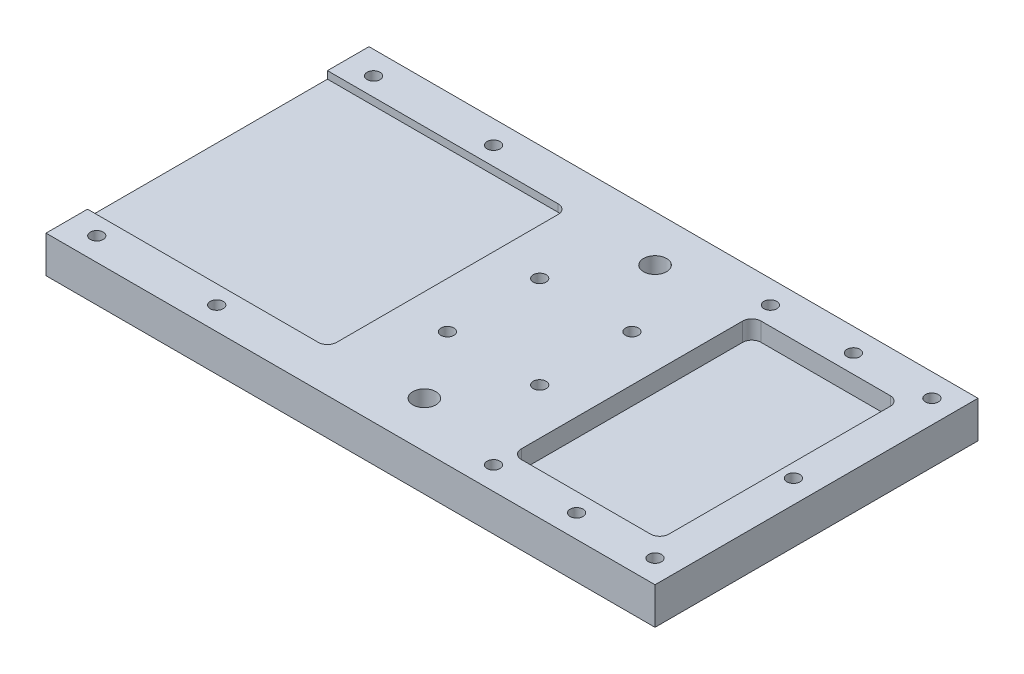
SolidWorks part; units mm, degrees
ref_plane "Front Plane" through (0, 0, 0) normal (0, 0, 1) x (1, 0, 0)
ref_plane "Top Plane" through (0, 0, 0) normal (0, 1, 0) x (1, 0, 0)
ref_plane "Right Plane" through (0, 0, 0) normal (1, 0, 0) x (0, 0, -1)
sketch "Sketch1" plane through (0, 0, 0) normal (0, 1, 0) x (1, 0, 0)
  line L1 (-50.8, -22.225) -> (50.8, -22.225)
  line L2 (-50.8, -22.225) -> (-50.8, 22.225)
  line L3 (-50.8, 22.225) -> (50.8, 22.225)
  line L4 (50.8, -22.225) -> (50.8, 22.225)
  line L5 (-50.8, -22.225) -> (50.8, 22.225) construction
  line L6 (-50.8, 22.225) -> (50.8, -22.225) construction
  point P0 (0, 0)
  dimension "D1" = 44.45
  dimension "D2" = 101.6
extrude "Boss-Extrude1" add sketch "Sketch1" along normal blind 5.08
sketch "Sketch2" plane through (0, 5.08, 0) normal (0, 1, 0) x (1, 0, 0)
  line L0 (-50.8, 0) -> (50.8, 0) construction
  line L1 (-50.8, 22.225) -> (-50.8, -22.225) construction
  line L2 (50.8, -22.225) -> (50.8, 22.225) construction
  line L3 (50.8, 19.05) -> (-50.8, 19.05) construction
  line L4 (50.8, -19.05) -> (-50.8, -19.05) construction
  line L5 (-50.8, -6.35) -> (50.8, -6.35) construction
  line L6 (-50.8, 6.35) -> (50.8, 6.35) construction
  line L7 (50.8, -22.225) -> (50.8, 22.225) construction
  circle A0 centre (-46.99, 19.05) radius 0.889
  circle A1 centre (-29.21, 19.05) radius 0.889
  circle A2 centre (-12.7, 19.05) radius 0.889
  circle A3 centre (25.4, 19.05) radius 0.889
  circle A4 centre (36.83, 19.05) radius 0.889
  circle A5 centre (47.625, 19.05) radius 0.889
  circle A6 centre (47.625, 0) radius 0.889
  circle A7 centre (47.625, -19.05) radius 0.889
  circle A8 centre (36.83, -19.05) radius 0.889
  circle A9 centre (25.4, -19.05) radius 0.889
  circle A10 centre (-12.7, -19.05) radius 0.889
  circle A11 centre (-29.21, -19.05) radius 0.889
  circle A12 centre (-46.99, -19.05) radius 0.889
  circle A13 centre (19.05, -6.35) radius 0.889
  circle A14 centre (19.05, 6.35) radius 0.889
  circle A15 centre (6.35, 6.35) radius 0.889
  circle A16 centre (6.35, -6.35) radius 0.889
  dimension "D3" = 1.778
  dimension "D4" = 1.778
  dimension "D5" = 1.778
  dimension "D6" = 1.778
  dimension "D7" = 1.778
  dimension "D8" = 1.778
  dimension "D9" = 1.778
  dimension "D10" = 1.778
  dimension "D11" = 1.778
  dimension "D12" = 1.778
  dimension "D13" = 1.778
  dimension "D14" = 1.778
  dimension "D15" = 1.778
  dimension "D18" = 1.778
  dimension "D19" = 1.778
  dimension "D20" = 1.778
  dimension "D21" = 1.778
  dimension "D1" = 19.05
  dimension "D2" = 19.05
  dimension "D16" = 6.35
  dimension "D17" = 6.35
  dimension "D22" = 3.81
  dimension "D23" = 21.59
  dimension "D24" = 38.1
  dimension "D25" = 57.15
  dimension "D26" = 69.85
  dimension "D27" = 76.2
  dimension "D28" = 87.63
  dimension "D29" = 98.425
extrude "Cut-Extrude1" cut sketch "Sketch2" against normal through all
sketch "Sketch3" plane through (0, 5.08, 0) normal (0, 1, 0) x (1, 0, 0)
  line L0 (-50.8, 0) -> (50.8, 0) construction
  line L1 (-50.8, 22.225) -> (-50.8, -22.225) construction
  line L2 (50.8, -22.225) -> (50.8, 22.225) construction
  circle A0 centre (-37.846, 19.3294) radius 1.2192
  circle A1 centre (12.7, 15.875) radius 1.5875
  dimension "D1" = 2.4384
  dimension "D2" = 3.175
  dimension "D3" = 63.5
  dimension "D4" = 15.875
  dimension "D5" = 12.954
  dimension "D6" = 19.3294
extrude "Cut-Extrude2" cut sketch "Sketch3" against normal through all
mirror "Mirror1" about plane through (0, 0, 0) normal (0, 0, 1) of "Cut-Extrude2"
sketch "Sketch4" plane through (0, 5.08, 0) normal (0, 1, 0) x (1, 0, 0)
  line L0 (-50.8, 22.225) -> (-50.8, -22.225) construction
  line L1 (-33.02, -17.018) -> (-50.8, -17.018)
  line L2 (-33.02, -17.018) -> (-33.02, 17.018)
  line L3 (-33.02, 17.018) -> (-50.8, 17.018)
  line L4 (-50.8, -17.018) -> (-50.8, 17.018)
  line L5 (-33.02, -17.018) -> (-50.8, 17.018) construction
  line L6 (-33.02, 17.018) -> (-50.8, -17.018) construction
  point P0 (-41.91, 0)
  dimension "D1" = 17.78
  dimension "D2" = 34.036
extrude "Cut-Extrude3" cut sketch "Sketch4" against normal through all
fillet "Fillet2" radius 2.54 2 edges at (-33.02, 2.54, 17.018) (-33.02, 2.54, -17.018)
sketch "Sketch5" plane through (0, 5.08, 0) normal (0, 1, 0) x (1, 0, 0)
  line L1 (-33.02, -22.225) -> (-50.8, -22.225)
  line L2 (-33.02, -22.225) -> (-33.02, 22.225)
  line L3 (-33.02, 22.225) -> (-50.8, 22.225)
  line L4 (-50.8, -22.225) -> (-50.8, 22.225)
  line L5 (-33.02, -22.225) -> (-50.8, 22.225) construction
  line L6 (-33.02, 22.225) -> (-50.8, -22.225) construction
  point P0 (-41.91, 0)
  dimension "D1" = 17.78
extrude "Cut-Extrude4" cut sketch "Sketch5" against normal through all
sketch "Sketch6" plane through (0, 5.08, 0) normal (0, 1, 0) x (1, 0, 0)
  line L0 (-33.02, -22.225) -> (-33.02, 22.225) construction
  line L1 (0, -16.51) -> (-33.02, -16.51)
  line L2 (0, -16.51) -> (0, 16.51)
  line L3 (0, 16.51) -> (-33.02, 16.51)
  line L4 (-33.02, -16.51) -> (-33.02, 16.51)
  line L5 (0, -16.51) -> (-33.02, 16.51) construction
  line L6 (0, 16.51) -> (-33.02, -16.51) construction
  point P0 (-16.51, 0)
  dimension "D1" = 16.51
  dimension "D2" = 33.02
extrude "Cut-Extrude5" cut sketch "Sketch6" against normal blind 1.016
fillet "Fillet3" radius 1.27 2 edges at (0, 4.572, -16.51) (0, 4.572, 16.51)
sketch "Sketch7" plane through (0, 5.08, 0) normal (0, 1, 0) x (1, 0, 0)
  line L0 (50.8, -22.225) -> (50.8, 22.225) construction
  line L1 (25.4, -16.5) -> (45.72, -16.5)
  line L2 (25.4, -16.5) -> (25.4, 16.5)
  line L3 (25.4, 16.5) -> (45.72, 16.5)
  line L4 (45.72, -16.5) -> (45.72, 16.5)
  line L5 (25.4, -16.5) -> (45.72, 16.5) construction
  line L6 (25.4, 16.5) -> (45.72, -16.5) construction
  point P0 (35.56, 0)
  dimension "D1" = 20.32
  dimension "D2" = 5.08
  dimension "D3" = 33
extrude "Cut-Extrude6" cut sketch "Sketch7" against normal blind 2.54
fillet "Fillet4" radius 1.27 4 edges at (45.72, 3.81, 16.5) (25.4, 3.81, 16.5) (45.72, 3.81, -16.5) (25.4, 3.81, -16.5)
